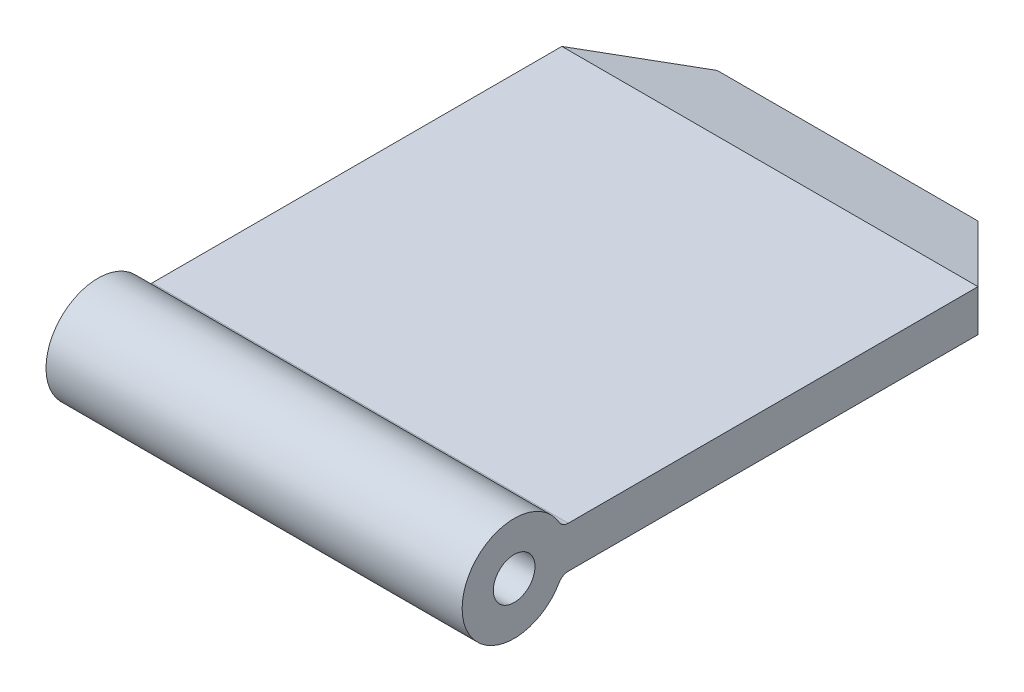
SolidWorks part; units mm, degrees
ref_plane "Front Plane" through (0, 0, 0) normal (0, 0, 1) x (1, 0, 0)
ref_plane "Top Plane" through (0, 0, 0) normal (0, 1, 0) x (1, 0, 0)
ref_plane "Right Plane" through (0, 0, 0) normal (1, 0, 0) x (0, 0, -1)
sketch "Sketch1" plane through (0, 0, 0) normal (1, 0, 0) x (0, 0, -1)
  line L6 (-15.7988, 0) -> (162.2339, 0) construction
  line L8 (11.6397, -5.08) -> (113.2397, -5.08)
  line L9 (113.2397, -5.08) -> (132.1986, 0)
  line L10 (113.2397, 5.08) -> (132.1986, 0)
  line L11 (11.6397, 5.08) -> (113.2397, 5.08)
  arc A9 (11.6397, 5.08) -> (11.6397, -5.08) centre (0, 0) ccw
  dimension "D1" = 25.4
  dimension "D2" = 101.6
  dimension "D3" = 15
  dimension "D4" = 5.08
extrude "Boss-Extrude1" add sketch "Sketch1" along normal blind 101.6
sketch "Sketch5" plane through (101.6, 0, 0) normal (1, 0, 0) x (0, 0, -1)
  circle A0 centre (0, 0) radius 5.08
  dimension "D1" = 10.16
extrude "Cut-Extrude4" cut sketch "Sketch5" against normal through all
sketch "Sketch6" plane through (0, 0, 0) normal (0, 1, 0) x (1, 0, 0)
  line L0 (0, 132.1986) -> (0, 113.2397)
  line L1 (0, 113.2397) -> (0, 11.6397) construction
  line L2 (0, 113.2397) -> (18.9588, 132.1986)
  line L3 (101.6, 132.1986) -> (0, 132.1986) construction
  line L4 (18.9588, 132.1986) -> (0, 132.1986)
  line L5 (50.8, -12.7) -> (50.8, 166.0068) construction
  line L6 (0, -12.7) -> (101.6, -12.7) construction
  line L7 (101.6, 132.1986) -> (101.6, 113.2397)
  line L8 (82.6412, 132.1986) -> (101.6, 132.1986)
  line L9 (101.6, 113.2397) -> (82.6412, 132.1986)
extrude "Cut-Extrude5" cut sketch "Sketch6" against normal through all both and the other way through all
fillet "Fillet1" radius 2.54 2 edges at (50.8, -5.08, -11.6397) (50.8, 5.08, -11.6397)
